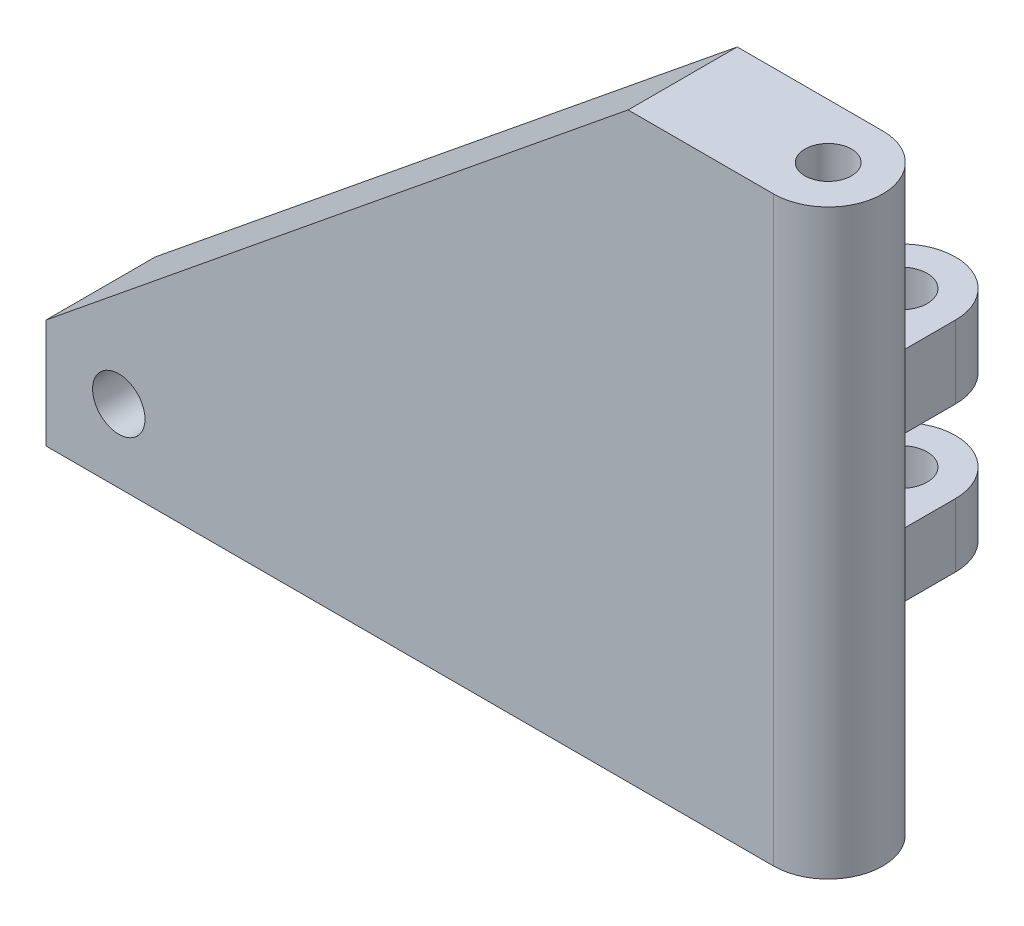
SolidWorks part; units mm, degrees
ref_plane "Front Plane" through (0, 0, 0) normal (0, 0, 1) x (1, 0, 0)
ref_plane "Top Plane" through (0, 0, 0) normal (0, 1, 0) x (1, 0, 0)
ref_plane "Right Plane" through (0, 0, 0) normal (1, 0, 0) x (0, 0, -1)
sketch "Sketch1" plane through (0, 0, 0) normal (0, 1, 0) x (1, 0, 0)
  line L0 (0, 4.7625) -> (-63.5, 4.7625)
  line L3 (0, -4.7625) -> (-63.5, -4.7625)
  line L4 (-63.5, 4.7625) -> (-63.5, -4.7625)
  arc A2 (0, -4.7625) -> (0, 4.7625) centre (0, 0) ccw
  circle A3 centre (0, 0) radius 2.032
  dimension "D2" = 63.5
  dimension "D1" = 4.7625
  dimension "D3" = 4.064
extrude "Boss-Extrude1" add sketch "Sketch1" along normal mid plane 50.8
sketch "Sketch5" plane through (0, -25.4, 0) normal (0, 1, 0) x (1, 0, 0)
  line L0 (-23.8125, 25.4) -> (-23.8125, 4.7625)
  line L1 (0, 4.7625) -> (-63.5, 4.7625) construction
  line L2 (-14.2875, 25.4) -> (-14.2875, 4.7625)
  line L3 (-23.8125, 4.7625) -> (-14.2875, 4.7625)
  arc A0 (-14.2875, 25.4) -> (-23.8125, 25.4) centre (-19.05, 25.4) ccw
  arc A1 (0, -4.7625) -> (0, 4.7625) centre (0, 0) ccw construction
  circle A2 centre (-19.05, 25.4) radius 2.286
  dimension "D1" = 25.4
  dimension "D3" = 4.572
  dimension "D2" = 19.05
extrude "Boss-Extrude2" add sketch "Sketch5" along normal blind 19.05
sketch "Sketch2" plane through (0, 0, 4.7625) normal (0, 0, 1) x (1, 0, 0)
  line L0 (-63.5, 25.4) -> (-63.5, -25.4) construction
  line L1 (-63.5, -25.4) -> (0, -25.4) construction
  circle A0 centre (-57.15, -19.05) radius 2.286
  dimension "D1" = 4.572
  dimension "D2" = 6.35
  dimension "D3" = 6.35
extrude "Cut-Extrude1" cut sketch "Sketch2" against normal through all
sketch "Sketch3" plane through (0, -25.4, 0) normal (0, 1, 0) x (1, 0, 0)
  line L0 (-22.225, 19.9007) -> (-14.2875, 15.318)
  line L1 (-14.2875, 4.7625) -> (-14.2875, 25.4) construction
  line L2 (-14.2875, 15.318) -> (-14.2875, 25.4)
  line L3 (-23.8125, 25.4) -> (-23.8125, 21.1999)
  arc A0 (-23.8125, 21.1999) -> (-22.225, 19.9007) centre (-19.05, 25.4) ccw
  arc A1 (-14.2875, 25.4) -> (-23.8125, 25.4) centre (-19.05, 25.4) ccw
  point P1 (-21.2124, 19.4295)
  dimension "D1" = 12.7
  dimension "D2" = 60
extrude "Cut-Extrude2" cut sketch "Sketch3" against normal blind 7.1437 from offset 12.7
sketch "Sketch4" plane through (0, 0, -4.7625) normal (0, 0, -1) x (-1, 0, 0)
  line L6 (12.7, 25.4) -> (63.5, -15.875)
  line L7 (0, 25.4) -> (63.5, 25.4) construction
  line L8 (63.5, 25.4) -> (63.5, -25.4) construction
  line L9 (63.5, -15.875) -> (63.5, 25.4)
  line L10 (63.5, 25.4) -> (12.7, 25.4)
  line L11 (0, -25.4) -> (14.2875, -25.4) construction
  dimension "D1" = 9.525
  dimension "D2" = 50.8
extrude "Cut-Extrude3" cut sketch "Sketch4" against normal through all
